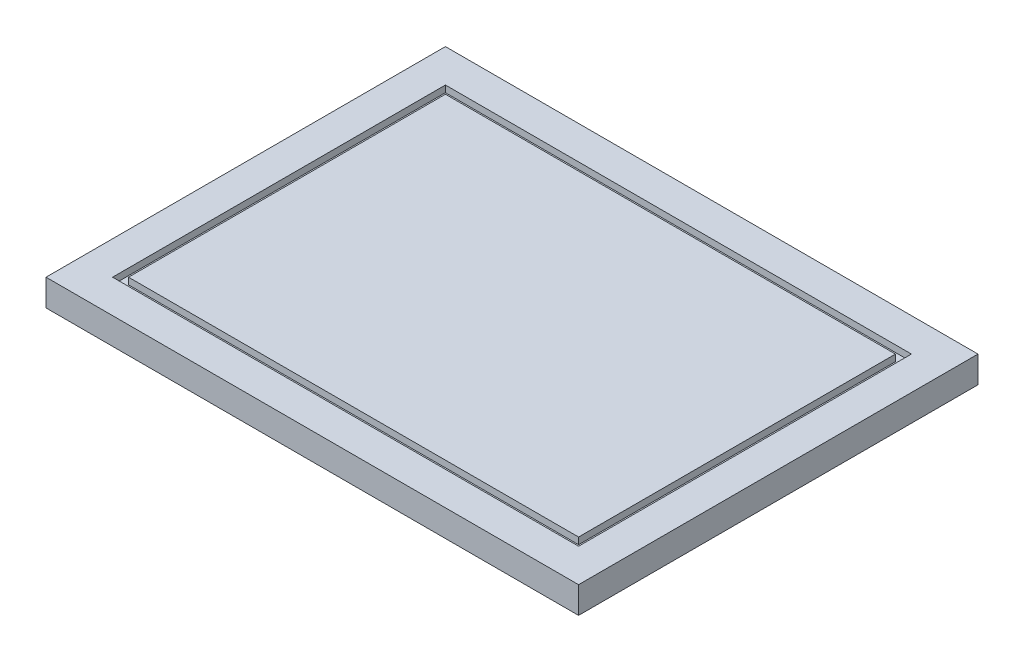
SolidWorks part; units mm, degrees
ref_plane "Front Plane" through (0, 0, 0) normal (0, 0, 1) x (1, 0, 0)
ref_plane "Top Plane" through (0, 0, 0) normal (0, 1, 0) x (1, 0, 0)
ref_plane "Right Plane" through (0, 0, 0) normal (1, 0, 0) x (0, 0, -1)
sketch "Sketch1" plane through (0, 0, 0) normal (0, 1, 0) x (1, 0, 0)
  line L1 (0, 0) -> (400, 0)
  line L2 (0, 0) -> (0, 300)
  line L3 (0, 300) -> (400, 300)
  line L4 (400, 0) -> (400, 300)
  dimension "D1" = 300
  dimension "D2" = 400
extrude "Boss-Extrude1" add sketch "Sketch1" along normal blind 20
sketch "Sketch2" plane through (0, 20, 0) normal (0, 1, 0) x (1, 0, 0)
  line L0 (25, 275) -> (25, 25)
  line L1 (25, 25) -> (375, 25)
  line L2 (375, 25) -> (375, 275)
  line L3 (375, 275) -> (25, 275)
  line L5 (400, 300) -> (0, 300) construction
  line L6 (400, 0) -> (400, 300) construction
  line L8 (31, 269) -> (369, 269)
  line L9 (31, 269) -> (31, 31)
  line L10 (31, 31) -> (369, 31)
  line L11 (369, 269) -> (369, 31)
  dimension "D1" = 250
  dimension "D2" = 350
  dimension "D3" = 25
  dimension "D4" = 25
  dimension "D5" = 6
  dimension "6" = 6
  dimension "D7" = 6
  dimension "D8" = 6
extrude "Cut-Extrude1" cut sketch "Sketch2" against normal blind 5
